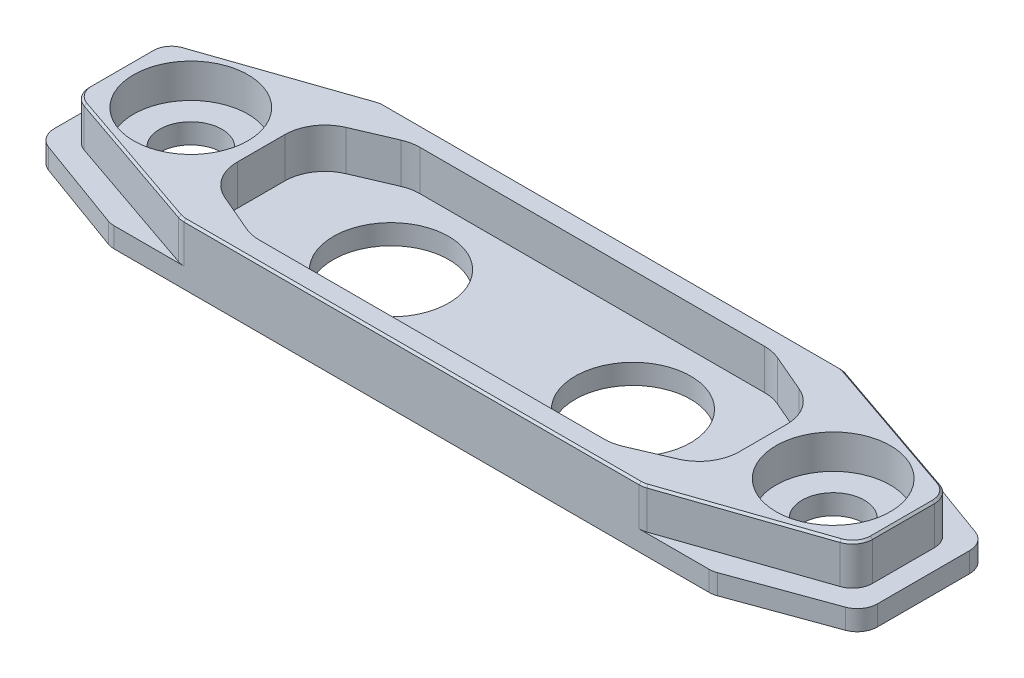
SolidWorks part; units mm, degrees
ref_plane "Front Plane" through (0, 0, 0) normal (0, 0, 1) x (1, 0, 0)
ref_plane "Top Plane" through (0, 0, 0) normal (0, 1, 0) x (1, 0, 0)
ref_plane "Right Plane" through (0, 0, 0) normal (1, 0, 0) x (0, 0, -1)
sketch "Sketch1" plane through (0, 0, 0) normal (0, 1, 0) x (1, 0, 0)
  line L1 (14.8238, -5) -> (-14.8238, -5)
  line L2 (20.5, -2.2996) -> (20.5, 2.2996)
  line L3 (14.8238, 5) -> (-14.8238, 5)
  line L4 (-20.5, -2.2996) -> (-20.5, 2.2996)
  line L5 (17.208, -4.1971) -> (-17.208, 4.1971) construction
  line L6 (17.208, 4.1971) -> (-17.208, -4.1971) construction
  line L10 (15.1656, 4.9398) -> (19.8417, 3.2394)
  line L11 (15.1656, -4.9398) -> (19.8417, -3.2394)
  line L12 (0, 6.8802) -> (0, -8.8637) construction
  line L13 (-15.1656, -4.9398) -> (-19.8417, -3.2394)
  line L14 (-15.1656, 4.9398) -> (-19.8417, 3.2394)
  arc A0 (-19.8417, 3.2394) -> (-20.5, 2.2996) centre (-19.5, 2.2996) ccw
  arc A1 (-15.1656, 4.9398) -> (-14.8238, 5) centre (-14.8238, 4) cw
  arc A2 (-19.8417, -3.2394) -> (-20.5, -2.2996) centre (-19.5, -2.2996) cw
  arc A3 (19.8417, -3.2394) -> (20.5, -2.2996) centre (19.5, -2.2996) ccw
  arc A4 (19.8417, 3.2394) -> (20.5, 2.2996) centre (19.5, 2.2996) cw
  arc A5 (15.1656, 4.9398) -> (14.8238, 5) centre (14.8238, 4) ccw
  arc A6 (14.8238, -5) -> (15.1656, -4.9398) centre (14.8238, -4) ccw
  arc A7 (-14.8238, -5) -> (-15.1656, -4.9398) centre (-14.8238, -4) cw
  point P0 (0, 0)
  point P8 (-20.5, 3)
  point P21 (-15, 5)
  point P24 (-20.5, -3)
  point P27 (20.5, -3)
  point P30 (20.5, 3)
  point P33 (15, 5)
  point P36 (15, -5)
  point P39 (-15, -5)
  dimension "D1" = 1
  dimension "D2" = 41
  dimension "D3" = 30
  dimension "D4" = 15
  dimension "D5" = 6
  dimension "D6" = 3
  dimension "D7" = 10
extrude "Boss-Extrude1" add sketch "Sketch1" along normal blind 1
sketch "Sketch2" plane through (0, 1, 0) normal (0, 1, 0) x (1, 0, 0)
  line L1 (11.3329, -5) -> (-11.3329, -5)
  line L2 (19.5, -1.5363) -> (19.5, 1.5363)
  line L3 (11.3329, 5) -> (-11.3329, 5)
  line L4 (-19.5, -1.5363) -> (-19.5, 1.5363)
  line L5 (14.9179, -3.8251) -> (-14.9179, 3.8251) construction
  line L6 (14.9179, 3.8251) -> (-14.9179, -3.8251) construction
  line L11 (11.658, 4.9457) -> (18.8251, 2.482)
  line L12 (11.658, -4.9457) -> (18.8251, -2.482)
  line L13 (0, 7.617) -> (0, -6.9064) construction
  line L14 (-11.658, -4.9457) -> (-18.8251, -2.482)
  line L15 (-11.658, 4.9457) -> (-18.8251, 2.482)
  arc A0 (-18.8251, 2.482) -> (-19.5, 1.5363) centre (-18.5, 1.5363) ccw
  arc A1 (-11.658, 4.9457) -> (-11.3329, 5) centre (-11.3329, 4) cw
  arc A2 (-18.8251, -2.482) -> (-19.5, -1.5363) centre (-18.5, -1.5363) cw
  arc A3 (-11.658, -4.9457) -> (-11.3329, -5) centre (-11.3329, -4) ccw
  arc A4 (18.8251, -2.482) -> (19.5, -1.5363) centre (18.5, -1.5363) ccw
  arc A5 (11.658, -4.9457) -> (11.3329, -5) centre (11.3329, -4) cw
  arc A6 (18.8251, 2.482) -> (19.5, 1.5363) centre (18.5, 1.5363) cw
  arc A7 (11.658, 4.9457) -> (11.3329, 5) centre (11.3329, 4) ccw
  point P0 (0, 0)
  point P7 (-19.5, 2.25)
  point P12 (-11.5, 5)
  point P24 (-19.5, -2.25)
  point P27 (-11.5, -5)
  point P30 (19.5, -2.25)
  point P33 (11.5, -5)
  point P36 (19.5, 2.25)
  point P39 (11.5, 5)
  dimension "D1" = 1
  dimension "D3" = 23
  dimension "D4" = 11.5
  dimension "D5" = 4.5
  dimension "D6" = 2.25
extrude "Boss-Extrude2" add sketch "Sketch2" along normal blind 2
sketch "Sketch3" plane through (0, 3, 0) normal (0, 1, 0) x (1, 0, 0)
  circle A0 centre (-16, 0) radius 1.55
  circle A1 centre (16, 0) radius 1.55
  dimension "D1" = 3.1
  dimension "D2" = 3.1
  dimension "D3" = 32
  dimension "D4" = 16
extrude "Cut-Extrude1" cut sketch "Sketch3" against normal through all
sketch "Sketch4" plane through (0, 3, 0) normal (0, 1, 0) x (1, 0, 0)
  circle A0 centre (-16, 0) radius 2.85
  circle A1 centre (16, 0) radius 2.85
  dimension "D1" = 5.7
  dimension "D2" = 5.7
extrude "Cut-Extrude2" cut sketch "Sketch4" against normal blind 1.7 and the other way blind 2
sketch "Sketch5" plane through (0, 3, 0) normal (0, 1, 0) x (1, 0, 0)
  line L1 (8.5895, -4) -> (-8.5895, -4)
  line L2 (12.5, -1.1812) -> (12.5, 1.1812)
  line L3 (8.5895, 4) -> (-8.5895, 4)
  line L4 (-12.5, -1.1812) -> (-12.5, 1.1812)
  line L5 (10.4962, -3.3588) -> (-10.4962, 3.3588) construction
  line L6 (10.4962, 3.3588) -> (-10.4962, -3.3588) construction
  line L10 (9.3773, 3.8383) -> (11.2878, 3.0195)
  line L11 (11.2878, -3.0195) -> (9.3773, -3.8383)
  line L12 (0, 7.7455) -> (0, -7.775) construction
  line L13 (-11.2878, -3.0195) -> (-9.3773, -3.8383)
  line L14 (-9.3773, 3.8383) -> (-11.2878, 3.0195)
  arc A0 (-11.2878, 3.0195) -> (-12.5, 1.1812) centre (-10.5, 1.1812) ccw
  arc A1 (-9.3773, 3.8383) -> (-8.5895, 4) centre (-8.5895, 2) cw
  arc A2 (-9.3773, -3.8383) -> (-8.5895, -4) centre (-8.5895, -2) ccw
  arc A3 (-11.2878, -3.0195) -> (-12.5, -1.1812) centre (-10.5, -1.1812) cw
  arc A4 (9.3773, -3.8383) -> (8.5895, -4) centre (8.5895, -2) cw
  arc A5 (11.2878, -3.0195) -> (12.5, -1.1812) centre (10.5, -1.1812) ccw
  arc A6 (11.2878, 3.0195) -> (12.5, 1.1812) centre (10.5, 1.1812) cw
  arc A7 (9.3773, 3.8383) -> (8.5895, 4) centre (8.5895, 2) ccw
  point P0 (0, 0)
  point P10 (-12.5, 2.5)
  point P23 (-9, 4)
  point P26 (-9, -4)
  point P29 (-12.5, -2.5)
  point P32 (9, -4)
  point P35 (12.5, -2.5)
  point P38 (12.5, 2.5)
  point P41 (9, 4)
  dimension "D1" = 2
  dimension "D3" = 5
  dimension "D4" = 2.5
  dimension "D5" = 18
  dimension "D6" = 9
extrude "Cut-Extrude3" cut sketch "Sketch5" against normal blind 2
sketch "Sketch6" plane through (0, 1, 0) normal (0, 1, 0) x (1, 0, 0)
  circle A0 centre (-6.025, 0) radius 2.875
  circle A1 centre (6.025, 0) radius 2.875
  dimension "D1" = 5.75
  dimension "D2" = 5.75
  dimension "D3" = 12.05
  dimension "D4" = 6.025
extrude "Cut-Extrude4" cut sketch "Sketch6" against normal through all
chamfer "Chamfer1" distance 0.1 angle 45 16 edges at (11.4977, 3, -4.9863) (0, 3, -5) (15.2415, 3, -3.7138) (-11.4977, 3, -4.9863) (19.314, 3, -2.1172) (-15.2415, 3, -3.7138) (19.5, 3, 0) (-19.314, 3, -2.1172) (19.314, 3, 2.1172) (-19.5, 3, 0) (15.2415, 3, 3.7138) (-19.314, 3, 2.1172) (11.4977, 3, 4.9863) (-15.2415, 3, 3.7138) (-11.4977, 3, 4.9863) (0, 3, 5)
sketch "Sketch7" plane through (0, 0, 0) normal (0, -1, 0) x (1, 0, 0)
  circle A0 centre (-16, 0) radius 4
  circle A1 centre (16, 0) radius 4
  dimension "D1" = 8
  dimension "D2" = 8
extrude "Cut-Extrude5" cut sketch "Sketch7" against normal blind 0.3
